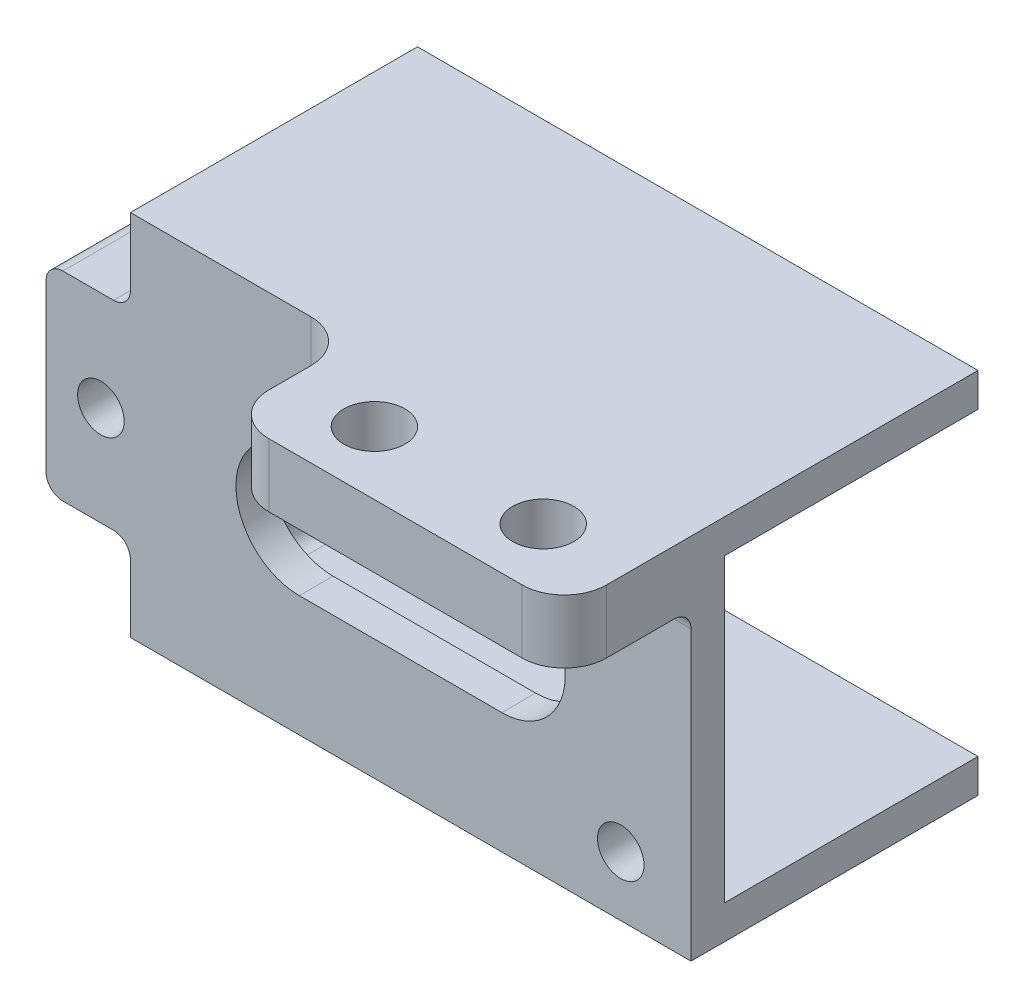
SolidWorks part; units mm, degrees
ref_plane "Front Plane" through (0, 0, 0) normal (0, 0, 1) x (1, 0, 0)
ref_plane "Top Plane" through (0, 0, 0) normal (0, 1, 0) x (1, 0, 0)
ref_plane "Right Plane" through (0, 0, 0) normal (1, 0, 0) x (0, 0, -1)
sketch "Sketch1" plane through (0, 0, 0) normal (0, 0, 1) x (1, 0, 0)
  line L0 (-2.54, 25.146) -> (39.624, 25.146)
  line L1 (0, 0) -> (37.084, 0)
  line L2 (0, 0) -> (0, 22.606)
  line L3 (0, 22.606) -> (37.084, 22.606)
  line L5 (39.624, -2.54) -> (39.624, 0)
  line L6 (-2.54, -2.54) -> (39.624, -2.54)
  line L7 (-2.54, -2.54) -> (-2.54, 25.146)
  line L8 (37.084, 0) -> (37.084, 22.606) construction
  line L9 (37.084, 22.606) -> (39.624, 22.606)
  line L10 (37.084, 0) -> (39.624, 0)
  line L11 (39.624, 22.606) -> (39.624, 25.146)
  line L12 (39.624, -2.54) -> (39.624, 25.146) construction
  dimension "D1" = 22.606
  dimension "D2" = 37.084
  dimension "D3" = 2.54
extrude "Boss-Extrude1" add sketch "Sketch1" along normal blind 19.05
sketch "Sketch2" plane through (0, 0, 19.05) normal (0, 0, 1) x (1, 0, 0)
  line L1 (-2.54, 25.146) -> (39.624, 25.146)
  line L2 (-2.54, 25.146) -> (-2.54, -2.54)
  line L3 (-2.54, -2.54) -> (39.624, -2.54)
  line L4 (39.624, 25.146) -> (39.624, -2.54)
extrude "Boss-Extrude2" add sketch "Sketch2" along normal blind 2.54
sketch "Sketch3" plane through (-2.54, 0, 0) normal (-1, 0, 0) x (0, 0, 1)
  line L1 (21.59, 18.796) -> (14.5288, 18.796)
  line L2 (21.59, 18.796) -> (21.59, 3.81)
  line L3 (21.59, 3.81) -> (14.5288, 3.81)
  line L4 (14.5288, 18.796) -> (14.5288, 3.81)
  line L5 (21.59, 25.146) -> (0, 25.146) construction
  line L6 (21.59, 25.146) -> (21.59, -2.54) construction
  line L7 (21.59, -2.54) -> (0, -2.54) construction
  dimension "D1" = 6.35
  dimension "D2" = 7.0612
  dimension "D3" = 6.35
extrude "Boss-Extrude3" add sketch "Sketch3" along normal blind 6.35
sketch "Sketch4" plane through (0, 0, 14.5288) normal (0, 0, -1) x (-1, 0, 0)
  line L1 (8.89, 18.796) -> (8.89, 3.81) construction
  line L2 (2.54, 25.146) -> (2.54, -2.54) construction
  circle A0 centre (4.7625, 11.303) radius 1.75
  point P6 (8.89, 11.303)
  dimension "D1" = 3.5
  dimension "D2" = 2.2225
extrude "Cut-Extrude1" cut sketch "Sketch4" against normal through all both and the other way through all
fillet "Fillet2" radius 1.27 4 edges at (-8.89, 3.81, 18.0594) (-2.54, 3.81, 18.0594) (-2.54, 18.796, 18.0594) (-8.89, 18.796, 18.0594)
sketch "Sketch5" plane through (0, 0, 21.59) normal (0, 0, 1) x (1, 0, 0)
  line L0 (39.624, -2.54) -> (39.624, 25.146) construction
  line L1 (-2.54, 20.066) -> (-2.54, 2.54) construction
  line L2 (10.16, 16.0655) -> (25.4, 16.0655)
  line L3 (10.16, 6.5405) -> (25.4, 6.5405)
  circle A0 centre (10.16, 11.303) radius 4.7625
  circle A1 centre (25.4, 11.303) radius 4.7625
  point P5 (39.624, 11.303)
  dimension "D1" = 9.525
  dimension "D2" = 12.7
  dimension "D3" = 15.24
extrude "Cut-Extrude2" cut sketch "Sketch5" against normal through all both contours A0 | A1 L2 A0 L3 | A1
sketch "Sketch6" plane through (0, 0, 21.59) normal (0, 0, 1) x (1, 0, 0)
  line L0 (39.624, 25.146) -> (-2.54, 25.146) construction
  line L1 (14.224, 25.146) -> (39.624, 25.146)
  line L2 (14.224, 25.146) -> (14.224, 20.3835)
  line L3 (14.224, 20.3835) -> (39.624, 20.3835)
  line L4 (39.624, 25.146) -> (39.624, 20.3835)
  line L7 (39.624, -2.54) -> (39.624, 25.146) construction
  point P6 (26.924, 20.3835)
  dimension "D1" = 4.7625
  dimension "D2" = 25.4
  dimension "D3" = 12.7
extrude "Boss-Extrude4" add sketch "Sketch6" along normal blind 9.525
fillet "Fillet3" radius 3.175 3 edges at (39.624, 22.7647, 31.115) (14.224, 22.7647, 31.115) (14.224, 22.7647, 21.59)
fillet "Fillet4" radius 1.27 1 edges at (25.3365, 20.3835, 21.59)
fillet "Fillet6" radius 1.27 2 edges at (0, 0, 9.525) (0, 22.606, 9.525)
sketch "Sketch8" plane through (0, 25.146, 0) normal (0, 1, 0) x (1, 0, 0)
  line L1 (14.224, -24.765) -> (14.224, -21.59) construction
  line L2 (26.924, -21.59) -> (26.924, -31.115) construction
  line L3 (36.449, -31.115) -> (17.399, -31.115) construction
  line L4 (14.224, -21.59) -> (26.924, -21.59) construction
  line L5 (26.924, -21.59) -> (39.624, -21.59) construction
  circle A0 centre (20.574, -26.3525) radius 2.3
  circle A1 centre (33.274, -26.3525) radius 2.3
  point P14 (26.924, -26.3525)
  point P15 (33.274, -21.59)
  point P16 (20.574, -21.59)
  dimension "D1" = 4.6
  dimension "D2" = 4.6
extrude "Cut-Extrude3" cut sketch "Sketch8" against normal through all both
sketch "Sketch9" plane through (0, 0, 0) normal (0, 0, -1) x (-1, 0, 0)
  line L0 (0, 1.27) -> (0, 21.336) construction
  line L1 (0, 16.383) -> (2.54, 16.383)
  line L2 (0, 16.383) -> (0, 6.223)
  line L3 (0, 6.223) -> (2.54, 6.223)
  line L4 (2.54, 16.383) -> (2.54, 6.223)
  line L5 (2.54, 20.066) -> (2.54, 2.54) construction
  point P8 (0, 11.303)
  dimension "D1" = 10.16
extrude "Cut-Extrude4" cut sketch "Sketch9" against normal up to surface (14.5288 mm away) up to face at (-4.7625, 9.553, 14.5288)
sketch "Sketch10" plane through (0, 0, 19.05) normal (0, 0, -1) x (-1, 0, 0)
  line L0 (-39.624, 0) -> (-39.624, 22.606) construction
  line L1 (-39.624, 0) -> (-1.27, 0) construction
  circle A0 centre (-34.344, 1.95) radius 1.75
  dimension "D1" = 3.5
  dimension "D2" = 5.28
  dimension "D3" = 1.95
extrude "Cut-Extrude5" cut sketch "Sketch10" against normal through all both and the other way through all
